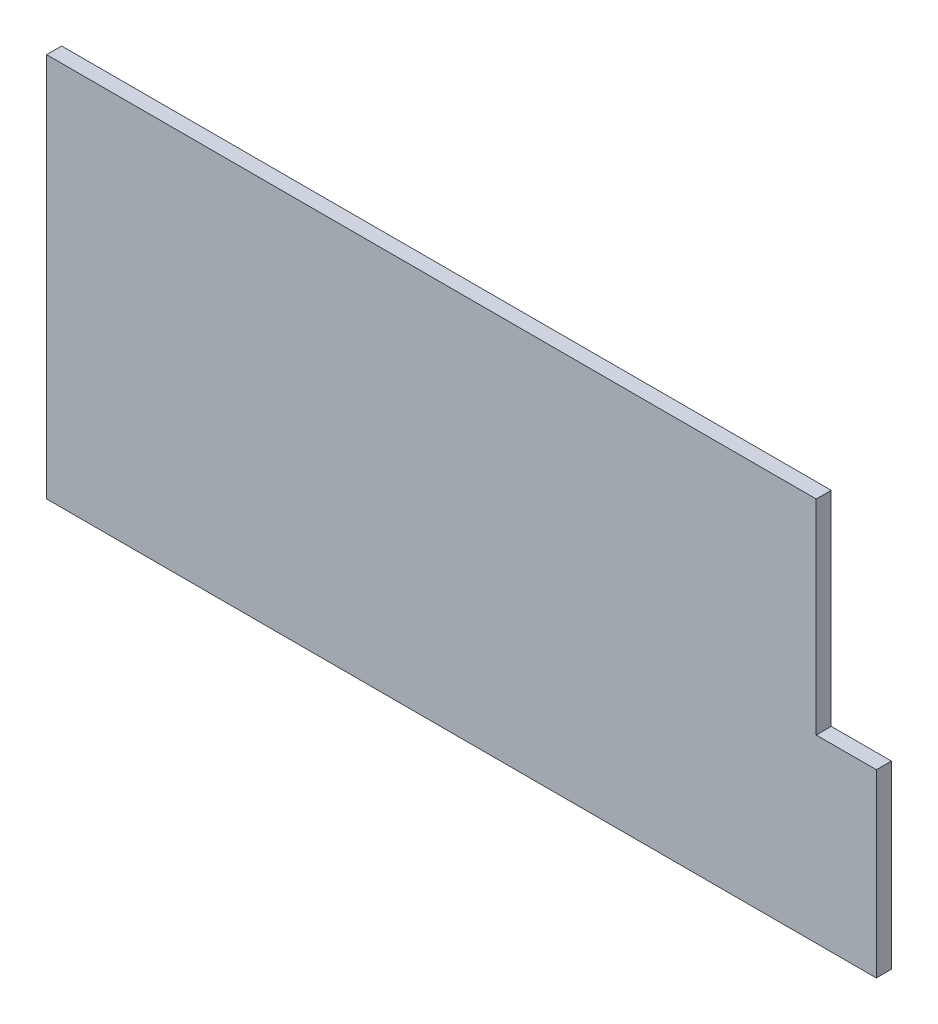
SolidWorks part; units mm, degrees
material "Hêtre"
ref_plane "Plan de face" through (0, 0, 0) normal (0, 0, 1) x (1, 0, 0)
ref_plane "Plan de dessus" through (0, 0, 0) normal (0, 1, 0) x (1, 0, 0)
ref_plane "Plan de droite" through (0, 0, 0) normal (1, 0, 0) x (0, 0, -1)
sketch "Esquisse1" plane through (0, 0, 0) normal (0, 0, 1) x (1, 0, 0)
  line L1 (0, 0) -> (276, 0)
  line L2 (0, 0) -> (0, 128)
  line L3 (0, 128) -> (256, 128)
  line L4 (276, 0) -> (276, 60)
  line L7 (276, 60) -> (256, 60)
  line L8 (256, 128) -> (256, 60)
  dimension "D1" = 128
  dimension "D2" = 276
  dimension "D3" = 20
  dimension "D4" = 60
extrude "Boss.-Extru.1" add sketch "Esquisse1" along normal blind 5
